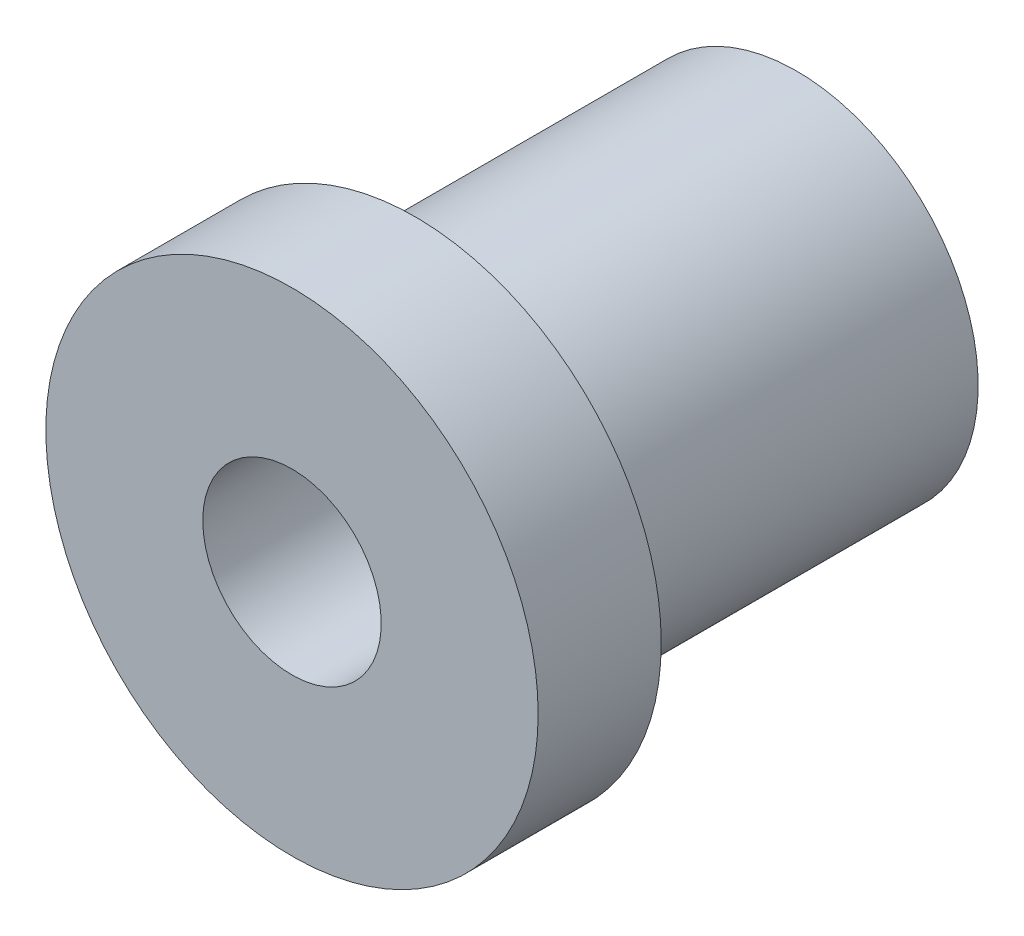
SolidWorks part; units mm, degrees
ref_plane "前视基准面" through (0, 0, 0) normal (0, 0, 1) x (1, 0, 0)
ref_plane "上视基准面" through (0, 0, 0) normal (0, 1, 0) x (1, 0, 0)
ref_plane "右视基准面" through (0, 0, 0) normal (1, 0, 0) x (0, 0, -1)
other "Configuration Table"
sketch "草图1" plane through (0, 0, 0) normal (0, 0, 1) x (1, 0, 0)
  circle A0 centre (0, 0) radius 1.45
  circle A2 centre (0, 0) radius 2.95
  dimension "D2" = 2.9
  dimension "D1" = 5.9
extrude "凸台-拉伸1" add sketch "草图1" along normal mid plane 6.2
sketch "草图2" plane through (0, 0, 3.1) normal (0, 0, 1) x (1, 0, 0)
  circle A0 centre (0, 0) radius 4
  circle A1 centre (0, 0) radius 1.45 construction
  circle A2 centre (0, 0) radius 1.45
  dimension "D1" = 8
extrude "凸台-拉伸2" add sketch "草图2" along normal blind 2
